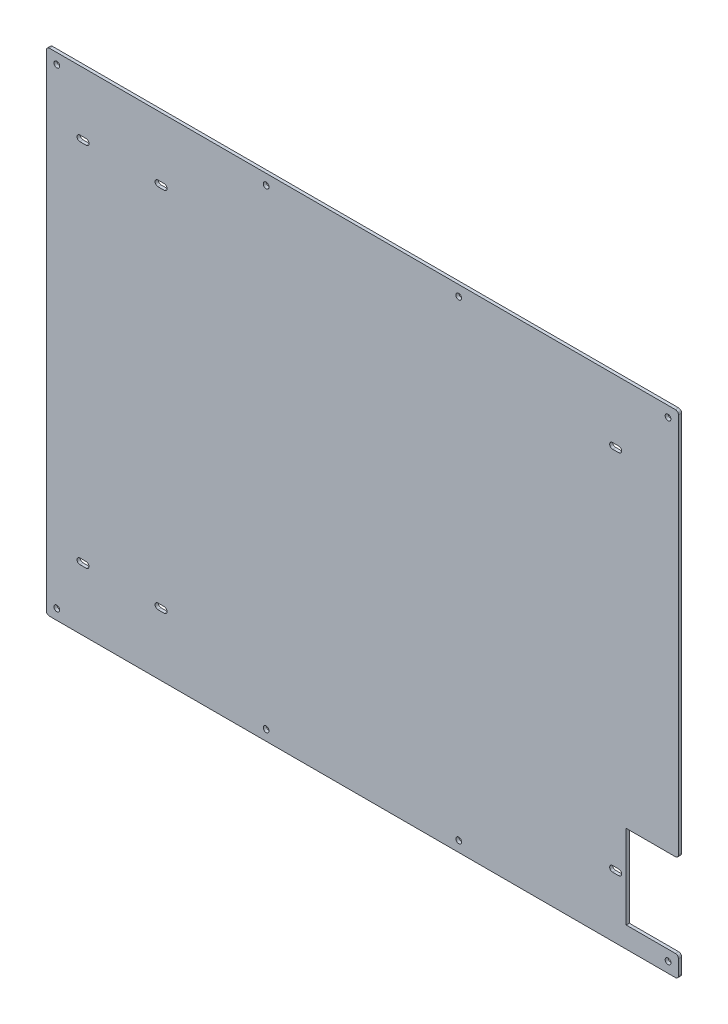
SolidWorks part; units mm, degrees
material "Acrylic (Medium-high impact)"
ref_plane "Front" through (0, 0, 0) normal (0, 0, 1) x (1, 0, 0)
ref_plane "Top" through (0, 0, 0) normal (0, 1, 0) x (1, 0, 0)
ref_plane "Right" through (0, 0, 0) normal (1, 0, 0) x (0, 0, -1)
sketch "Sketch1" plane through (0, 0, 0) normal (0, 0, 1) x (1, 0, 0)
  line L0 (0, 450) -> (604, 450) construction
  line L1 (0, 0) -> (604, 0)
  line L2 (0, 0) -> (0, 470)
  line L3 (0, 470) -> (604, 470)
  line L4 (604, 0) -> (604, 470)
  dimension "D1" = 604
  dimension "D2" = 470
  dimension "D3" = 20
extrude "Boss-Extrude1" add sketch "Sketch1" along normal blind 3
fillet "Fillet1" radius 3 4 edges at (0, 0, 1.5) (604, 0, 1.5) (0, 470, 1.5) (604, 470, 1.5)
hole_wizard "M5 Clearance Hole1" positions "Sketch4" profile "Sketch3" hole size "M5" standard "ANSI Metric" end condition through all
sketch "Sketch4" plane through (0, 0, 0) normal (0, 0, -1) x (-1, 0, 0)
  line L0 (-210, 460) -> (-10, 460) construction
  line L1 (-10, 460) -> (0, 460) construction
  line L2 (0, 467) -> (0, 3) construction
  line L5 (-210, 460) -> (-246, 460) construction
  line L8 (-302, 470) -> (-302, 460) construction
  line L9 (-601, 470) -> (-3, 470) construction
  line L10 (-358, 460) -> (-246, 460) construction
  line L14 (-394, 460) -> (-358, 460) construction
  line L15 (-594, 460) -> (-604, 460) construction
  line L16 (-394, 460) -> (-594, 460) construction
  line L17 (-10, 10) -> (0, 10) construction
  line L20 (-10, 10) -> (-210, 10) construction
  line L21 (-210, 10) -> (-246, 10) construction
  line L22 (-246, 10) -> (-358, 10) construction
  line L27 (-210, 460) -> (-210, 10) construction
  line L30 (-10, 10) -> (-10, 460) construction
  line L32 (-394, 10) -> (-358, 10) construction
  line L33 (-594, 10) -> (-394, 10) construction
  line L34 (-594, 10) -> (-604, 10) construction
  line L35 (-3, 0) -> (-601, 0) construction
  line L36 (-544, 470) -> (-544, 410) construction
  line L37 (-601, 470) -> (-3, 470) construction
  line L38 (-544, 410) -> (-544, 60) construction
  line L39 (-544, 60) -> (-544, 0) construction
  line L40 (-3, 0) -> (-601, 0) construction
  line L43 (-604, 3) -> (-604, 467) construction
  line L44 (-35, 470) -> (-35, 410) construction
  line L45 (-35, 410) -> (-35, 60) construction
  line L46 (-35, 60) -> (-35, 0) construction
  line L49 (0, 467) -> (0, 3) construction
  line L50 (-109.625, 470) -> (-109.625, 410) construction
  line L51 (-109.625, 410) -> (-109.625, 60) construction
  line L52 (-109.625, 60) -> (-109.625, 0) construction
  point P0 (-594, 460)
  point P2 (-394, 460)
  point P4 (-210, 460)
  point P6 (-10, 460)
  point P8 (-10, 10)
  point P10 (-210, 10)
  point P12 (-394, 10)
  point P14 (-594, 10)
  point P98 (-544, 410)
  point P102 (-544, 60)
  point P120 (-35, 410)
  point P122 (-35, 60)
  point P138 (-109.625, 410)
  point P140 (-109.625, 60)
  dimension "D1" = 10
  dimension "D2" = 200
  dimension "D4" = 10
  dimension "D5" = 10
  dimension "D6" = 60
  dimension "D7" = 60
  dimension "D8" = 35
  dimension "D9" = 109.625
sketch "Sketch3" plane through (594, 460, 0) normal (1, 0, 0) x (0, 1, 0)
  line L0 (0, 0) -> (0, 3)
  line L1 (0, 3) -> (2.75, 3)
  line L2 (2.75, 3) -> (2.75, 0)
  line L5 (2.75, 0) -> (0, 0)
  line L11 (0, -6.35) -> (0, 107.95) construction
  dimension "Thru Hole Dia." = 5.5
  dimension "Thru Hole Depth" = 3
sketch "Sketch5" plane through (0, 0, 3) normal (0, 0, 1) x (1, 0, 0)
  line L0 (3, 0) -> (601, 0) construction
  line L1 (566.25, 20) -> (594.25, 20)
  line L2 (566.25, 20) -> (566.25, 67)
  line L3 (566.25, 67) -> (594.25, 67)
  line L4 (594.25, 20) -> (594.25, 67)
  line L5 (604, 3) -> (604, 467) construction
  line L6 (566.25, 43.5) -> (560.25, 43.5) construction
  line L7 (580.25, 67) -> (580.25, 20) construction
  line L9 (545.25, 14.25) -> (573.25, 14.25) construction
  circle A0 centre (560.25, 43.5) radius 1.6
  circle A1 centre (600.25, 43.5) radius 1.6
  circle A2 centre (394, 10) radius 4.75 construction
  circle A4 centre (594, 10) radius 4.75 construction
  dimension "D5" = 3.2
  dimension "D6" = 40
  dimension "D3" = 3.75
  dimension "D7" = 9.5
  dimension "D1" = 20
  dimension "D2" = 47
  dimension "D4" = 28
  dimension "D8" = 5.75
extrude "PSU Cutout" [suppressed] cut sketch "Sketch5" against normal through all
fillet "Fillet2" [suppressed] radius 0.5
sketch "Sketch9" plane through (0, 0, 3) normal (0, 0, 1) x (1, 0, 0)
  line L0 (32, 410) -> (38, 410) construction
  line L1 (32, 412.75) -> (38, 412.75)
  line L2 (32, 407.25) -> (38, 407.25)
  line L3 (106.625, 410) -> (112.625, 410) construction
  line L4 (106.625, 412.75) -> (112.625, 412.75)
  line L5 (106.625, 407.25) -> (112.625, 407.25)
  line L6 (32, 60) -> (38, 60) construction
  line L7 (32, 62.75) -> (38, 62.75)
  line L8 (32, 57.25) -> (38, 57.25)
  line L9 (106.625, 60) -> (112.625, 60) construction
  line L10 (106.625, 62.75) -> (112.625, 62.75)
  line L11 (106.625, 57.25) -> (112.625, 57.25)
  line L12 (541, 410) -> (547, 410) construction
  line L13 (541, 412.75) -> (547, 412.75)
  line L14 (541, 407.25) -> (547, 407.25)
  line L15 (541, 60) -> (547, 60) construction
  line L16 (541, 62.75) -> (547, 62.75)
  line L17 (541, 57.25) -> (547, 57.25)
  arc A0 (32, 412.75) -> (32, 407.25) centre (32, 410) ccw
  arc A1 (38, 407.25) -> (38, 412.75) centre (38, 410) ccw
  circle A2 centre (35, 410) radius 2.75 construction
  arc A3 (106.625, 412.75) -> (106.625, 407.25) centre (106.625, 410) ccw
  arc A4 (112.625, 407.25) -> (112.625, 412.75) centre (112.625, 410) ccw
  circle A5 centre (109.625, 410) radius 2.75 construction
  arc A6 (32, 62.75) -> (32, 57.25) centre (32, 60) ccw
  arc A7 (38, 57.25) -> (38, 62.75) centre (38, 60) ccw
  arc A8 (106.625, 62.75) -> (106.625, 57.25) centre (106.625, 60) ccw
  arc A9 (112.625, 57.25) -> (112.625, 62.75) centre (112.625, 60) ccw
  arc A10 (541, 412.75) -> (541, 407.25) centre (541, 410) ccw
  arc A11 (547, 407.25) -> (547, 412.75) centre (547, 410) ccw
  arc A12 (541, 62.75) -> (541, 57.25) centre (541, 60) ccw
  arc A13 (547, 57.25) -> (547, 62.75) centre (547, 60) ccw
  circle A14 centre (544, 410) radius 2.75 construction
  circle A15 centre (544, 410) radius 2.75 construction
  circle A16 centre (544, 60) radius 2.75 construction
  circle A17 centre (544, 60) radius 2.75 construction
  circle A18 centre (35, 60) radius 2.75 construction
  circle A19 centre (35, 60) radius 2.75 construction
  circle A20 centre (109.625, 60) radius 2.75 construction
  circle A21 centre (109.625, 60) radius 2.75 construction
  circle A22 centre (35, 410) radius 2.75 construction
  circle A23 centre (109.625, 410) radius 2.75 construction
  point P2 (35, 410)
  point P12 (109.625, 410)
  point P22 (35, 60)
  point P29 (109.625, 60)
  point P37 (544, 410)
  point P45 (544, 60)
  dimension "D1" = 6
extrude "Cut-Extrude5" cut sketch "Sketch9" against normal through all
sketch "Sketch6" [suppressed] plane through (0, 0, 3) normal (0, 0, 1) x (1, 0, 0)
  line L0 (604, 3) -> (604, 467) construction
  line L1 (604, 396) -> (562, 396)
  line L2 (604, 396) -> (604, 194)
  line L3 (604, 194) -> (562, 194)
  line L4 (562, 396) -> (562, 194)
  line L5 (601, 470) -> (3, 470) construction
  dimension "D1" = 42
  dimension "D2" = 202
  dimension "D3" = 276
extrude "Cut-Extrude2" [suppressed] cut sketch "Sketch6" against normal through all
other "Move Face1" [suppressed] parameters "D1"=0.0762
fillet "Fillet3" [suppressed] radius 3
sketch "Sketch7" [suppressed] plane through (0, 0, 3) normal (0, 0, 1) x (1, 0, 0)
  line L0 (523, 0) -> (523, 70) construction
  line L1 (3, 0) -> (601, 0) construction
  line L2 (523, 70) -> (604, 70) construction
  line L3 (604, 3) -> (604, 467) construction
  line L4 (513, 0) -> (513, 80)
  line L5 (513, 80) -> (604, 80)
  line L6 (604, 80) -> (604, 470)
  line L7 (604, 470) -> (0, 470)
  line L8 (0, 470) -> (0, 0)
  line L9 (0, 0) -> (513, 0)
  line L10 (601, 470) -> (3, 470) construction
  circle A0 centre (523, 60) radius 2.75 construction
  dimension "D1" = 10
  dimension "D2" = 10
  dimension "D3" = 10
extrude "Cut-Extrude3" [suppressed] cut sketch "Sketch7" against normal through all
fillet "Fillet4" [suppressed] radius 3
sketch "Sketch8" [suppressed] plane through (0, 0, 3) normal (0, 0, 1) x (1, 0, 0)
  line L0 (523, 60) -> (523, 10) construction
  line L1 (523, 10) -> (599, 10) construction
  circle A0 centre (523, 10) radius 2.65
  dimension "D1" = 5.3
extrude "Cut-Extrude4" [suppressed] cut sketch "Sketch8" against normal through all
other "Move Face2" [suppressed] parameters "D1"=0.0762
sketch "Sketch10" plane through (0, 0, 3) normal (0, 0, 1) x (1, 0, 0)
  line L1 (604, 20) -> (554, 20)
  line L2 (604, 20) -> (604, 100)
  line L3 (604, 100) -> (554, 100)
  line L4 (554, 20) -> (554, 100)
  line L5 (604, 3) -> (604, 467) construction
  line L6 (3, 0) -> (601, 0) construction
  dimension "D1" = 80
  dimension "D2" = 50
  dimension "D3" = 20
extrude "Cut-Extrude6" cut sketch "Sketch10" against normal through all
fillet "Fillet5" radius 3 2 edges at (604, 100, 1.5) (604, 20, 1.5)
